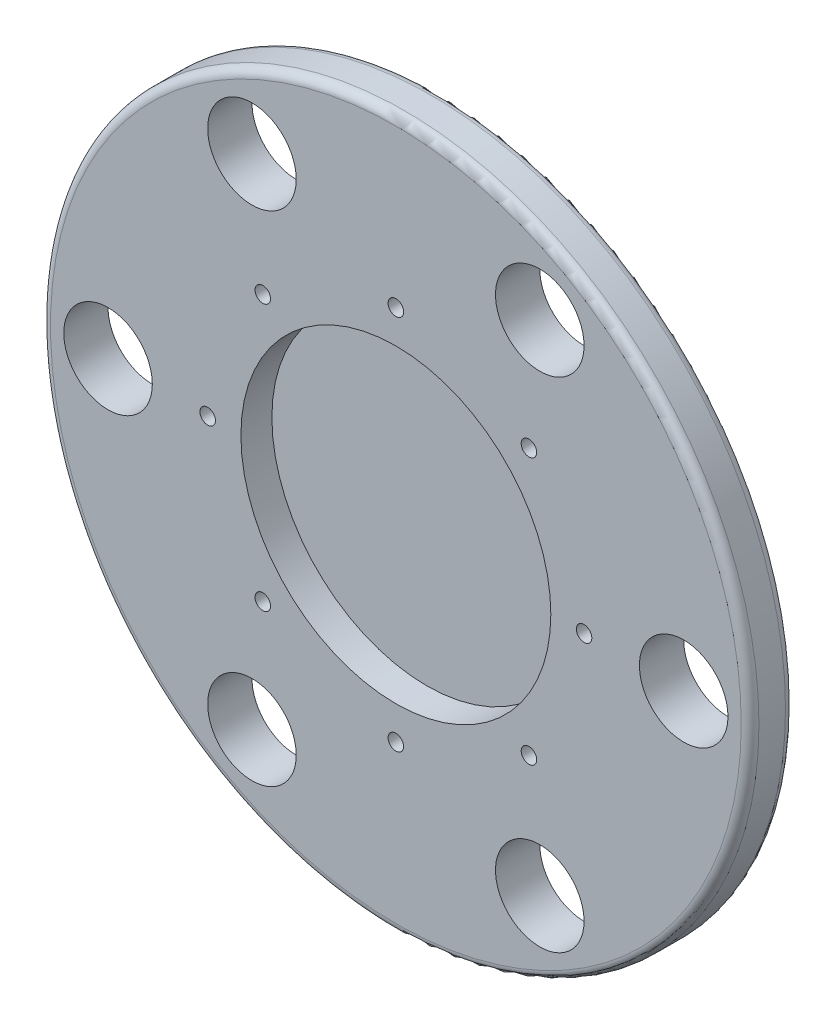
SolidWorks part; units mm, degrees
ref_plane "前视基准面" through (0, 0, 0) normal (0, 0, 1) x (1, 0, 0)
ref_plane "上视基准面" through (0, 0, 0) normal (0, 1, 0) x (1, 0, 0)
ref_plane "右视基准面" through (0, 0, 0) normal (1, 0, 0) x (0, 0, -1)
sketch "草图3" plane through (0, 0, 0) normal (0, 0, 1) x (1, 0, 0)
  circle A0 centre (0, 0) radius 80
extrude "凸台-拉伸1" add sketch "草图3" against normal blind 10
sketch "草图4" plane through (0, 0, 0) normal (0, 0, 1) x (1, 0, 0)
  circle A0 centre (0, 0) radius 35
  dimension "D1" = 70
extrude "切除-拉伸1" cut sketch "草图4" against normal blind 7
sketch "草图5" plane through (0, 0, 0) normal (0, 0, 1) x (1, 0, 0)
  circle A0 centre (0, 0) radius 65 construction
  circle A1 centre (-65, 0) radius 10
  circle A2 centre (0.0005, 0.0009) radius 65 construction
  circle A3 centre (-32.4995, 56.2925) radius 10
  circle A4 centre (0.0015, 0.0009) radius 65 construction
  circle A5 centre (32.5015, 56.2925) radius 10
  circle A6 centre (0.002, 0) radius 65 construction
  circle A7 centre (65.002, 0) radius 10
  circle A8 centre (0.0015, -0.0009) radius 65 construction
  circle A9 centre (32.5015, -56.2925) radius 10
  circle A10 centre (0.0005, -0.0009) radius 65 construction
  circle A11 centre (-32.4995, -56.2925) radius 10
  point P28 (0.001, 0)
  dimension "D1" = 20
  dimension "D3" = 130
  dimension "D2" = 65
  dimension "D4" = 6
extrude "切除-拉伸2" cut sketch "草图5" against normal blind 10
sketch "草图6" plane through (0, 0, 0) normal (0, 0, 1) x (1, 0, 0)
  circle A1 centre (0, 0) radius 42.5 construction
  circle A2 centre (-42.5, 0) radius 1.75
  circle A3 centre (-30.052, 30.052) radius 1.75
  circle A4 centre (0, 42.5) radius 1.75
  circle A5 centre (30.052, 30.052) radius 1.75
  circle A6 centre (42.5, 0) radius 1.75
  circle A7 centre (30.052, -30.052) radius 1.75
  circle A8 centre (0, -42.5) radius 1.75
  circle A9 centre (-30.052, -30.052) radius 1.75
  point P22 (0, 0)
  dimension "D1" = 85
  dimension "D2" = 3.5
  dimension "D3" = 8
extrude "切除-拉伸3" cut sketch "草图6" against normal blind 10
fillet "圆角1" radius 2 2 edges at (80, 0, -10) (80, 0, 0)
